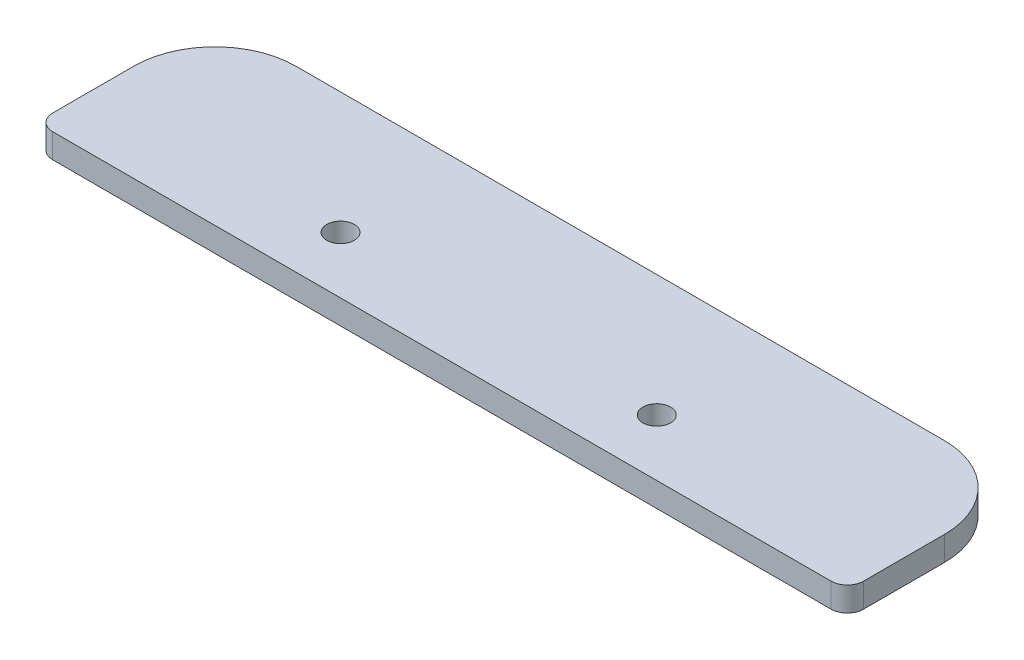
SolidWorks part; units mm, degrees
ref_plane "Front Plane" through (0, 0, 0) normal (0, 0, 1) x (1, 0, 0)
ref_plane "Top Plane" through (0, 0, 0) normal (0, 1, 0) x (1, 0, 0)
ref_plane "Right Plane" through (0, 0, 0) normal (1, 0, 0) x (0, 0, -1)
sketch "Sketch1" plane through (0, 12, 0) normal (0, 1, 0) x (1, 0, 0)
  line L0 (50, -49) -> (50, 18.1911) construction
  line L1 (-50, 50) -> (50, 50)
  line L3 (-50, 28) -> (50, 28)
  line L5 (-50, 50) -> (-50, 28)
  line L6 (50, 50) -> (50, 28)
  dimension "D1" = 22
extrude "Boss-Extrude1" add sketch "Sketch1" along normal blind 3
sketch "Sketch2" plane through (0, 15, 0) normal (0, 1, 0) x (1, 0, 0)
  line L0 (50, 50) -> (-50, 50) construction
  line L1 (50, 28) -> (50, 50) construction
  circle A0 centre (-19.5, 35) radius 1.7
  circle A1 centre (19.5, 35) radius 1.7
  dimension "D1" = 3.4
  dimension "D2" = 3.4
  dimension "D3" = 15
  dimension "D4" = 15
  dimension "D5" = 39
  dimension "D6" = 30.5
extrude "Cut-Extrude1" cut sketch "Sketch2" against normal up to surface (3 mm away) up to face at (0, 12, -39)
fillet "Fillet1" radius 10 2 edges at (-50, 13.5, -50) (50, 13.5, -50)
fillet "Fillet2" radius 2 2 edges at (-50, 13.5, -28) (50, 13.5, -28)
